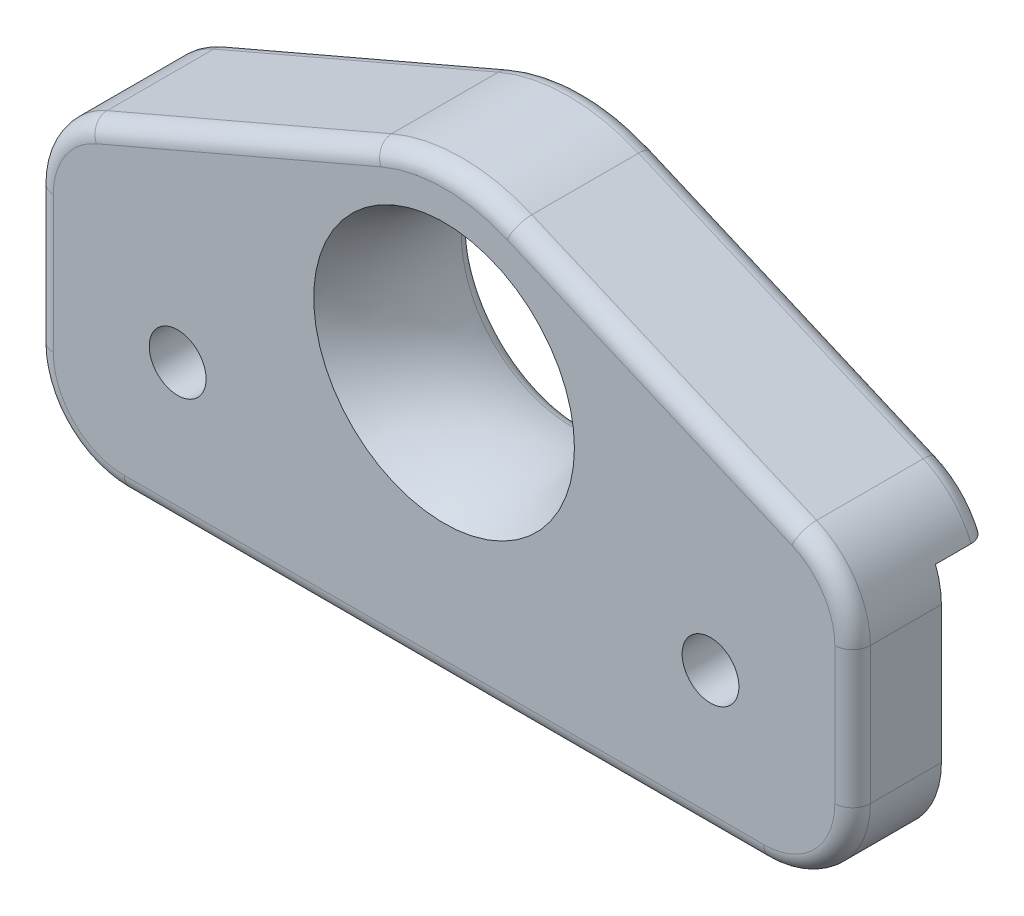
SolidWorks part; units mm, degrees
material "ABS"
ref_plane "Front" through (0, 0, 0) normal (0, 0, 1) x (1, 0, 0)
ref_plane "Top" through (0, 0, 0) normal (0, 1, 0) x (1, 0, 0)
ref_plane "Right" through (0, 0, 0) normal (1, 0, 0) x (0, 0, -1)
sketch "Esquisse1" plane through (0, 0, 0) normal (0, 0, 1) x (1, 0, 0)
  line L0 (-23, 1) -> (-3.9484, 9.1875)
  line L1 (-23, 1) -> (23, 1) construction
  line L2 (-23, 1) -> (-23, -15)
  line L3 (-23, -15) -> (23, -15)
  line L4 (23, 1) -> (23, -15)
  line L5 (3.9484, 9.1875) -> (23, 1)
  line L6 (0, -50) -> (0, 50) construction
  arc A0 (-3.9484, 9.1875) -> (3.9484, 9.1875) centre (0, 0) cw
  circle A1 centre (-15, -7) radius 1.6
  circle A2 centre (15, -7) radius 1.6
  point P4 (0, -15)
  dimension "D1" = 7
  dimension "D2" = 8
  dimension "D3" = 3.2
  dimension "D4" = 30
  dimension "D6" = 10
  dimension "D5" = 8
  dimension "D7" = 8
extrude "Boss.-Extru.1" add sketch "Esquisse1" along normal blind 8
sketch "Esquisse2" plane through (23, 0, 0) normal (1, 0, 0) x (0, 0, -1)
  line L1 (0, -15) -> (-3, -15)
  line L2 (0, -15) -> (0, -0.5)
  line L3 (0, -0.5) -> (-3, -0.5)
  line L4 (-3, -15) -> (-3, -0.5)
  dimension "D1" = 0.5
  dimension "D2" = 3
extrude "Enlèv. mat.-Extru.1" cut sketch "Esquisse2" against normal through all
sketch "Esquisse5" plane through (0, 0, 0) normal (0, 0, -1) x (-1, 0, 0)
  circle A0 centre (0, 0) radius 8
  dimension "D1" = 16
extrude "Boss.-Extru.2" add sketch "Esquisse5" against normal up to surface (3 mm away) up to face at (-13.4, -7, 3)
sketch "Esquisse4" plane through (0, 0, 0) normal (1, 0, 0) x (0, 0, -1)
  line L0 (-8, 0) -> (0, 0)
  line L1 (0, 0) -> (0, 6.4606)
  line L2 (-8, 7.3397) -> (-8, 0)
  line L5 (-3, -0.5) -> (-3, -15) construction
  line L6 (0, -0.5) -> (0, 1) construction
  line L7 (-8, -15) -> (-8, 1) construction
  arc A0 (0, 6.4606) -> (-8, 7.3397) centre (-3, 16) cw
  dimension "D1" = 6
  dimension "D2" = 10
revolve "Enlèvement de matière-Révolution1" cut sketch "Esquisse4" angle 360 about L0
fillet "Congé1" radius 5 4 edges at (-23, -15, 5.5) (-23, 1, 4) (23, -15, 5.5) (23, 1, 4)
fillet "Congé2" radius 1 16 edges at (21.6039, 1.1725, 0) (11.9613, 5.7439, 0) (-21.6039, 1.1725, 0) (-11.9613, 5.7439, 0) (11.9613, 5.7439, 8) (22.1756, 0.457, 8) (23, -6.1467, 8) (21.5355, -13.5355, 8) (0, -15, 8) (-21.5355, -13.5355, 8) (-23, -6.1467, 8) (-22.1756, 0.457, 8) (-11.9613, 5.7439, 8) (0, 10, 0) (0, 10, 8) (6.4606, 0, 0)
sketch "Esquisse6" plane through (0, 0, 8) normal (0, 0, 1) x (1, 0, 0)
  line L5 (19.5793, 1.3816) -> (3.5535, 8.2688)
  line L6 (-3.5535, 8.2688) -> (-19.5793, 1.3816)
  line L7 (-22, -2.2934) -> (-22, -10)
  line L8 (-18, -14) -> (18, -14)
  line L9 (22, -10) -> (22, -2.2934)
  line L10 (19.5793, 1.3816) -> (3.5535, 8.2688)
  line L11 (-3.5535, 8.2688) -> (-19.5793, 1.3816)
  line L12 (-22, -2.2934) -> (-22, -10)
  line L13 (-18, -14) -> (18, -14)
  line L14 (22, -10) -> (22, -2.2934)
  arc A5 (22, -2.2934) -> (19.5793, 1.3816) centre (18, -2.2934) ccw
  arc A6 (3.5535, 8.2688) -> (-3.5535, 8.2688) centre (0, 0) ccw
  arc A7 (-19.5793, 1.3816) -> (-22, -2.2934) centre (-18, -2.2934) ccw
  arc A8 (-22, -10) -> (-18, -14) centre (-18, -10) ccw
  arc A9 (18, -14) -> (22, -10) centre (18, -10) ccw
  arc A10 (22, -2.2934) -> (19.5793, 1.3816) centre (18, -2.2934) ccw
  arc A11 (3.5535, 8.2688) -> (-3.5535, 8.2688) centre (0, 0) ccw
  arc A12 (-19.5793, 1.3816) -> (-22, -2.2934) centre (-18, -2.2934) ccw
  arc A13 (-22, -10) -> (-18, -14) centre (-18, -10) ccw
  arc A14 (18, -14) -> (22, -10) centre (18, -10) ccw
  dimension "D1" = 0
extrude "Boss.-Extru.3" [suppressed] add sketch "Esquisse6" against normal blind 0.2
